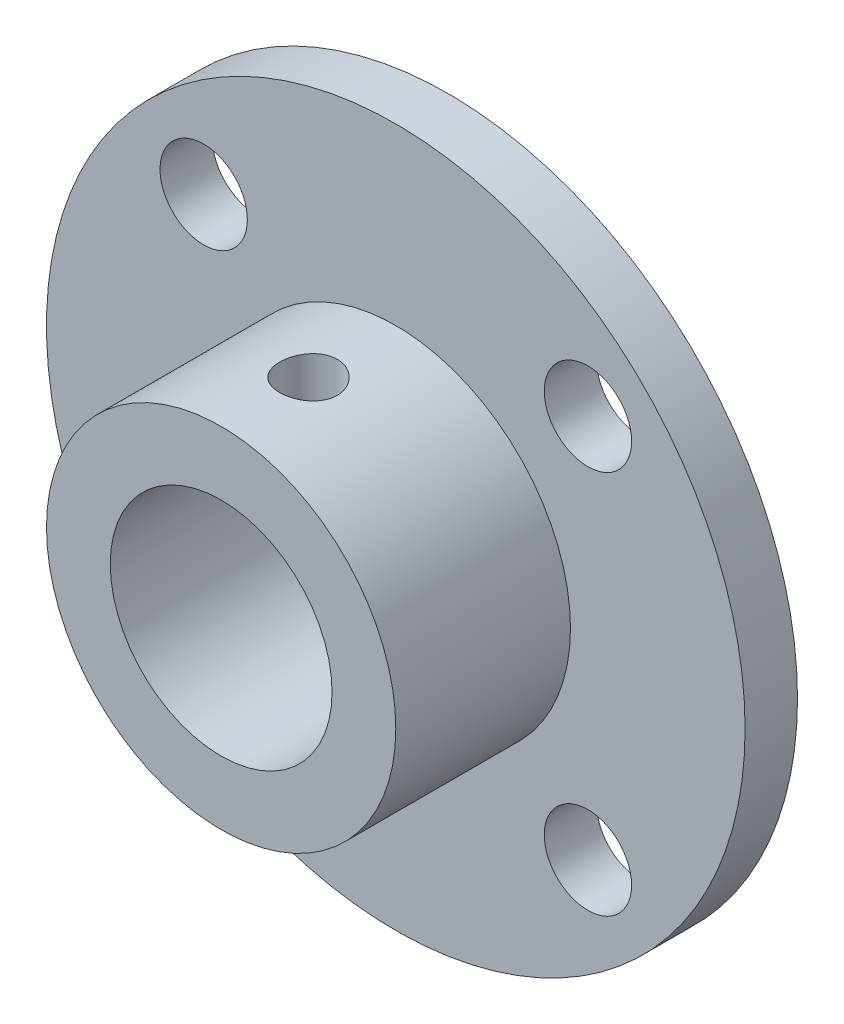
SolidWorks part; units mm, degrees
ref_plane "Front Plane" through (0, 0, 0) normal (0, 0, 1) x (1, 0, 0)
ref_plane "Top Plane" through (0, 0, 0) normal (0, 1, 0) x (1, 0, 0)
ref_plane "Right Plane" through (0, 0, 0) normal (1, 0, 0) x (0, 0, -1)
sketch "Sketch1" plane through (0, 0, 0) normal (0, 0, 1) x (1, 0, 0)
  circle A0 centre (0, 0) radius 20
  dimension "D1" = 40
extrude "Boss-Extrude1" add sketch "Sketch1" along normal blind 3
sketch "Sketch2" plane through (0, 0, 3) normal (0, 0, 1) x (1, 0, 0)
  circle A0 centre (0, 0) radius 10
  dimension "D1" = 20
extrude "Boss-Extrude2" add sketch "Sketch2" along normal blind 10
sketch "Sketch4" plane through (0, 0, 13) normal (0, 0, 1) x (1, 0, 0)
  circle A0 centre (0, 0) radius 6.35
  dimension "D1" = 12.7
extrude "Cut-Extrude1" cut sketch "Sketch4" against normal through all
ref_plane "Plane2" through (0, 0, 8) normal (0, 0, 1) x (1, 0, 0)
hole_wizard "M4 Tapped Hole1" positions "3DSketch7" profile "Sketch15" tap size "M4" standard "ISO"
sketch3d "3DSketch7"
  point P0 (0, 10, 8)
sketch "Sketch15" plane through (0, 10, 8) normal (1, 0, 0) x (0, 0, 1)
  line L0 (0, 0) -> (0, 3.65)
  line L1 (0, 3.65) -> (1.65, 3.65)
  line L2 (1.65, 3.65) -> (1.65, 0)
  line L5 (1.65, 0) -> (0, 0)
  line L11 (0, -6.35) -> (0, 107.95) construction
  dimension "Thru Tap Drill Dia." = 3.3
  dimension "Thru Tap Drill Depth" = 3.65
cosmetic thread "Hole Thread1" parameters "D2"=4
sketch "Sketch16" plane through (0, 0, 3) normal (0, 0, 1) x (1, 0, 0)
  line L0 (0, 0) -> (34.2865, 0) construction
  line L1 (0, 0) -> (11, 11) construction
  point P0 (11, 11)
  dimension "D1" = 11
  dimension "D2" = 45
hole_wizard "Ø5.0 (5) Diameter Hole1" positions "3DSketch8" profile "Sketch17" hole size "Ø5.0" standard "ISO" end condition through all
sketch3d "3DSketch8"
  point P0 (11, 11, 3)
sketch "Sketch17" plane through (11, 11, 3) normal (1, 0, 0) x (0, -1, 0)
  line L0 (0, 0) -> (0, 3)
  line L1 (0, 3) -> (2.5, 3)
  line L2 (2.5, 3) -> (2.5, 0)
  line L5 (2.5, 0) -> (0, 0)
  line L11 (0, -6.35) -> (0, 107.95) construction
  dimension "Thru Hole Dia." = 5
  dimension "Thru Hole Depth" = 3
pattern_circular "CirPattern1" count 4 over 360 about axis through (0, 0, 0) along (0, 0, 1) of "Ø5.0 (5) Diameter Hole1"
